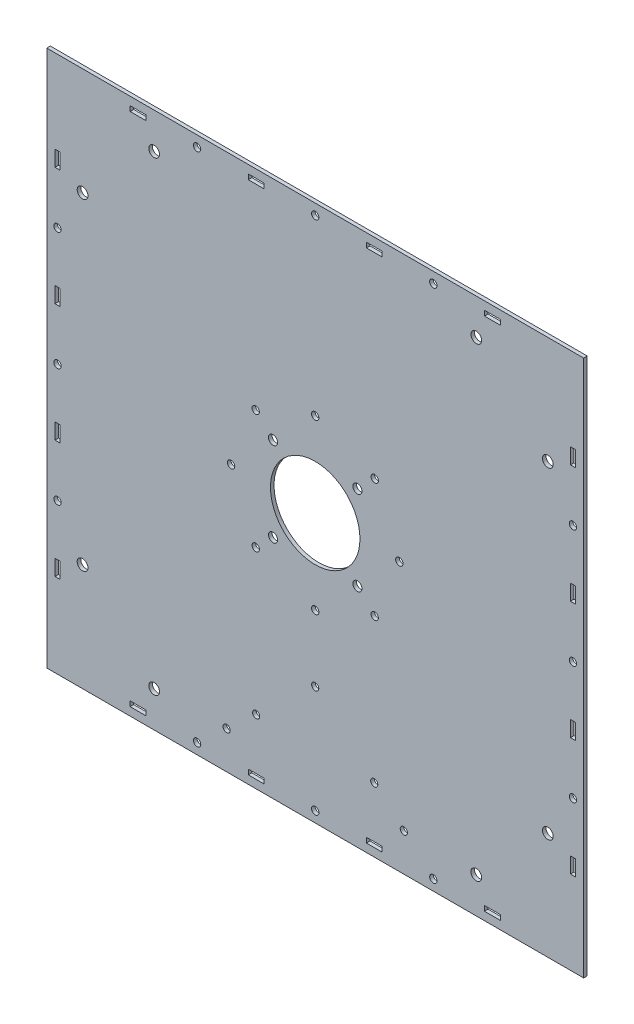
SolidWorks part; units mm, degrees
ref_plane "前视基准面" through (0, 0, 0) normal (0, 0, 1) x (1, 0, 0)
ref_plane "上视基准面" through (0, 0, 0) normal (0, 1, 0) x (1, 0, 0)
ref_plane "右视基准面" through (0, 0, 0) normal (1, 0, 0) x (0, 0, -1)
sketch "草图1" plane through (0, 0, 0) normal (0, 0, 1) x (1, 0, 0)
  line L0 (1.4571, -21.1871) -> (1.4571, -41.1871) construction
  line L2 (1.4571, -21.1871) -> (1.4571, 44.8129) construction
  line L4 (151.4571, -41.1871) -> (151.4571, 108.8129)
  line L5 (151.4571, 108.8129) -> (-148.5429, 108.8129)
  line L6 (-148.5429, 108.8129) -> (-148.5429, -191.1871)
  line L7 (-148.5429, -191.1871) -> (151.4571, -191.1871)
  line L8 (151.4571, -191.1871) -> (151.4571, -41.1871)
  line L9 (-148.5429, -41.1871) -> (-161.9412, -41.1871) construction
  line L10 (1.4571, -191.1871) -> (1.4571, -181.0361) construction
  circle A6 centre (1.4571, -21.1871) radius 241.4173 construction
  circle A9 centre (1.4571, -41.1871) radius 25
  circle A10 centre (25.0271, -17.6171) radius 2.55
  circle A11 centre (25.0271, -64.7571) radius 2.55
  circle A12 centre (-22.1129, -64.7571) radius 2.55
  circle A13 centre (-22.1129, -17.6171) radius 2.55
  dimension "D1" = 50
  dimension "D4" = 5.1
  dimension "D2" = 300
  dimension "D3" = 300
  dimension "D5" = 23.57
  dimension "D6" = 23.57
  dimension "D7" = 4
extrude "凸台-拉伸1" add sketch "草图1" along normal blind 2
sketch "草图3" plane through (0, 0, 2) normal (0, 0, 1) x (1, 0, 0)
  line L1 (96.0571, -183.7871) -> (104.8571, -183.7871)
  line L13 (1.4571, -191.1871) -> (1.4571, -185.1871) construction
  line L14 (-148.5429, -191.1871) -> (151.4571, -191.1871) construction
  line L15 (1.4571, -185.1871) -> (34.4571, -185.1871) construction
  line L16 (34.4571, -185.1871) -> (67.4571, -185.1871) construction
  line L17 (30.0571, -183.7871) -> (38.8571, -183.7871)
  line L18 (30.0571, -183.7871) -> (30.0571, -186.5871)
  line L19 (30.0571, -186.5871) -> (38.8571, -186.5871)
  line L20 (38.8571, -183.7871) -> (38.8571, -186.5871)
  line L21 (30.0571, -183.7871) -> (38.8571, -186.5871) construction
  line L22 (30.0571, -186.5871) -> (38.8571, -183.7871) construction
  line L23 (67.4571, -185.1871) -> (100.4571, -185.1871) construction
  line L24 (96.0571, -183.7871) -> (96.0571, -186.5871)
  line L25 (96.0571, -186.5871) -> (104.8571, -186.5871)
  line L26 (96.0571, -186.5871) -> (104.8571, -183.7871) construction
  line L27 (104.8571, -186.5871) -> (104.8571, -183.7871)
  line L28 (-35.9429, -183.7871) -> (-35.9429, -186.5871)
  line L29 (-27.1429, -183.7871) -> (-35.9429, -183.7871)
  line L30 (-27.1429, -183.7871) -> (-27.1429, -186.5871)
  line L31 (-27.1429, -186.5871) -> (-35.9429, -186.5871)
  line L32 (-93.1429, -183.7871) -> (-93.1429, -186.5871)
  line L33 (-101.9429, -186.5871) -> (-101.9429, -183.7871)
  line L34 (-93.1429, -183.7871) -> (-101.9429, -183.7871)
  line L35 (-93.1429, -186.5871) -> (-101.9429, -186.5871)
  line L36 (-141.1429, 53.4129) -> (-141.1429, 62.2129)
  line L37 (-143.9429, 53.4129) -> (-143.9429, 62.2129)
  line L38 (-143.9429, 62.2129) -> (-141.1429, 62.2129)
  line L39 (-141.1429, 53.4129) -> (-143.9429, 53.4129)
  line L40 (-141.1429, -12.5871) -> (-141.1429, -3.7871)
  line L41 (-141.1429, -3.7871) -> (-143.9429, -3.7871)
  line L42 (-143.9429, -12.5871) -> (-143.9429, -3.7871)
  line L43 (-141.1429, -12.5871) -> (-143.9429, -12.5871)
  line L44 (-141.1429, -69.7871) -> (-143.9429, -69.7871)
  line L45 (-141.1429, -69.7871) -> (-141.1429, -78.5871)
  line L46 (-143.9429, -69.7871) -> (-143.9429, -78.5871)
  line L47 (-141.1429, -78.5871) -> (-143.9429, -78.5871)
  line L48 (-141.1429, -135.7871) -> (-141.1429, -144.5871)
  line L49 (-143.9429, -135.7871) -> (-143.9429, -144.5871)
  line L50 (-141.1429, -135.7871) -> (-143.9429, -135.7871)
  line L51 (-143.9429, -144.5871) -> (-141.1429, -144.5871)
  line L52 (96.0571, 101.4129) -> (104.8571, 101.4129)
  line L53 (96.0571, 104.2129) -> (104.8571, 104.2129)
  line L54 (104.8571, 104.2129) -> (104.8571, 101.4129)
  line L55 (96.0571, 101.4129) -> (96.0571, 104.2129)
  line L56 (30.0571, 101.4129) -> (38.8571, 101.4129)
  line L57 (38.8571, 101.4129) -> (38.8571, 104.2129)
  line L58 (30.0571, 104.2129) -> (38.8571, 104.2129)
  line L59 (30.0571, 101.4129) -> (30.0571, 104.2129)
  line L60 (-27.1429, 101.4129) -> (-27.1429, 104.2129)
  line L61 (-27.1429, 101.4129) -> (-35.9429, 101.4129)
  line L62 (-27.1429, 104.2129) -> (-35.9429, 104.2129)
  line L63 (-35.9429, 101.4129) -> (-35.9429, 104.2129)
  line L64 (-93.1429, 101.4129) -> (-101.9429, 101.4129)
  line L65 (-93.1429, 104.2129) -> (-101.9429, 104.2129)
  line L66 (-93.1429, 101.4129) -> (-93.1429, 104.2129)
  line L67 (-101.9429, 104.2129) -> (-101.9429, 101.4129)
  line L68 (144.0571, -135.7871) -> (144.0571, -144.5871)
  line L69 (146.8571, -135.7871) -> (146.8571, -144.5871)
  line L70 (146.8571, -144.5871) -> (144.0571, -144.5871)
  line L71 (144.0571, -135.7871) -> (146.8571, -135.7871)
  line L72 (144.0571, -69.7871) -> (144.0571, -78.5871)
  line L73 (144.0571, -78.5871) -> (146.8571, -78.5871)
  line L74 (146.8571, -69.7871) -> (146.8571, -78.5871)
  line L75 (144.0571, -69.7871) -> (146.8571, -69.7871)
  line L76 (144.0571, -12.5871) -> (146.8571, -12.5871)
  line L77 (144.0571, -12.5871) -> (144.0571, -3.7871)
  line L78 (146.8571, -12.5871) -> (146.8571, -3.7871)
  line L79 (144.0571, -3.7871) -> (146.8571, -3.7871)
  line L80 (144.0571, 53.4129) -> (144.0571, 62.2129)
  line L81 (146.8571, 53.4129) -> (146.8571, 62.2129)
  line L82 (144.0571, 53.4129) -> (146.8571, 53.4129)
  line L83 (146.8571, 62.2129) -> (144.0571, 62.2129)
  line L84 (50.9571, -185.1871) -> (50.9571, -170.1871) construction
  line L85 (17.9571, -185.1871) -> (17.9571, -170.1871) construction
  line L86 (-48.0429, -170.1871) -> (-15.0429, -170.1871) construction
  line L91 (-31.5429, -170.1871) -> (-31.5429, -155.1871) construction
  line L92 (100.4571, -185.1871) -> (104.8571, -186.5871) construction
  circle A0 centre (1.4571, -185.1871) radius 2.05
  circle A1 centre (67.4571, -185.1871) radius 2.05
  circle A2 centre (-64.5429, -185.1871) radius 2.05
  circle A3 centre (-142.5429, 24.8129) radius 2.05
  circle A4 centre (-142.5429, -41.1871) radius 2.05
  circle A5 centre (-142.5429, -107.1871) radius 2.05
  circle A6 centre (67.4571, 102.8129) radius 2.05
  circle A7 centre (1.4571, 102.8129) radius 2.05
  circle A8 centre (-64.5429, 102.8129) radius 2.05
  circle A9 centre (145.4571, -107.1871) radius 2.05
  circle A10 centre (145.4571, -41.1871) radius 2.05
  circle A11 centre (145.4571, 24.8129) radius 2.05
  circle A15 centre (17.9571, -170.1871) radius 2 construction
  circle A16 centre (-15.0429, -170.1871) radius 2 construction
  circle A17 centre (50.9571, -170.1871) radius 2
  circle A18 centre (-48.0429, -170.1871) radius 2
  circle A19 centre (-31.5429, -155.1871) radius 2
  circle A20 centre (34.4571, -155.1871) radius 2
  circle A22 centre (1.4571, -155.1871) radius 2 construction
  circle A23 centre (1.4571, -41.1871) radius 47 construction
  circle A24 centre (1.4571, -88.1871) radius 2.05
  circle A25 centre (-31.7769, -74.4212) radius 2.05
  circle A26 centre (-45.5429, -41.1871) radius 2.05
  circle A27 centre (-31.7769, -7.9531) radius 2.05
  circle A28 centre (1.4571, 5.8129) radius 2.05
  circle A29 centre (34.6912, -7.9531) radius 2.05
  circle A30 centre (48.4571, -41.1871) radius 2.05
  circle A31 centre (34.6912, -74.4212) radius 2.05
  circle A32 centre (1.4571, -125.1871) radius 2
  dimension "D1" = 8.8
  dimension "D3" = 4
  dimension "D4" = 8
  dimension "D5" = 30
  dimension "D6" = 4.1
  dimension "D7" = 94
  dimension "D8" = 4
  dimension "D9" = 8.8
  dimension "D2" = 2.8
  dimension "D10" = 2.8
extrude "切除-拉伸2" cut sketch "草图3" against normal blind 4
sketch "草图6" plane through (0, 0, 2) normal (0, 0, 1) x (1, 0, 0)
sketch "草图7" plane through (0, 0, 2) normal (0, 0, 1) x (1, 0, 0)
  line L5 (-148.5429, -171.1871) -> (151.4571, -171.1871) construction
  line L6 (-148.5429, 108.8129) -> (-148.5429, -191.1871) construction
  line L7 (151.4571, -191.1871) -> (151.4571, 108.8129) construction
  line L8 (-148.5429, -191.1871) -> (151.4571, -191.1871) construction
  circle A0 centre (-88.5429, -171.1871) radius 3
  circle A1 centre (91.4571, -171.1871) radius 3
  circle A2 centre (-128.5429, 48.8129) radius 3
  circle A3 centre (-128.5429, -131.1871) radius 3
  circle A4 centre (91.4571, 88.8129) radius 3
  circle A5 centre (-88.5429, 88.8129) radius 3
  circle A6 centre (131.4571, -131.1871) radius 3
  circle A7 centre (131.4571, 48.8129) radius 3
  dimension "D2" = 6
  dimension "D4" = 60
  dimension "D1" = 20
  dimension "D3" = 60
  dimension "D5" = 4
extrude "切除-拉伸3" cut sketch "草图7" against normal blind 10
